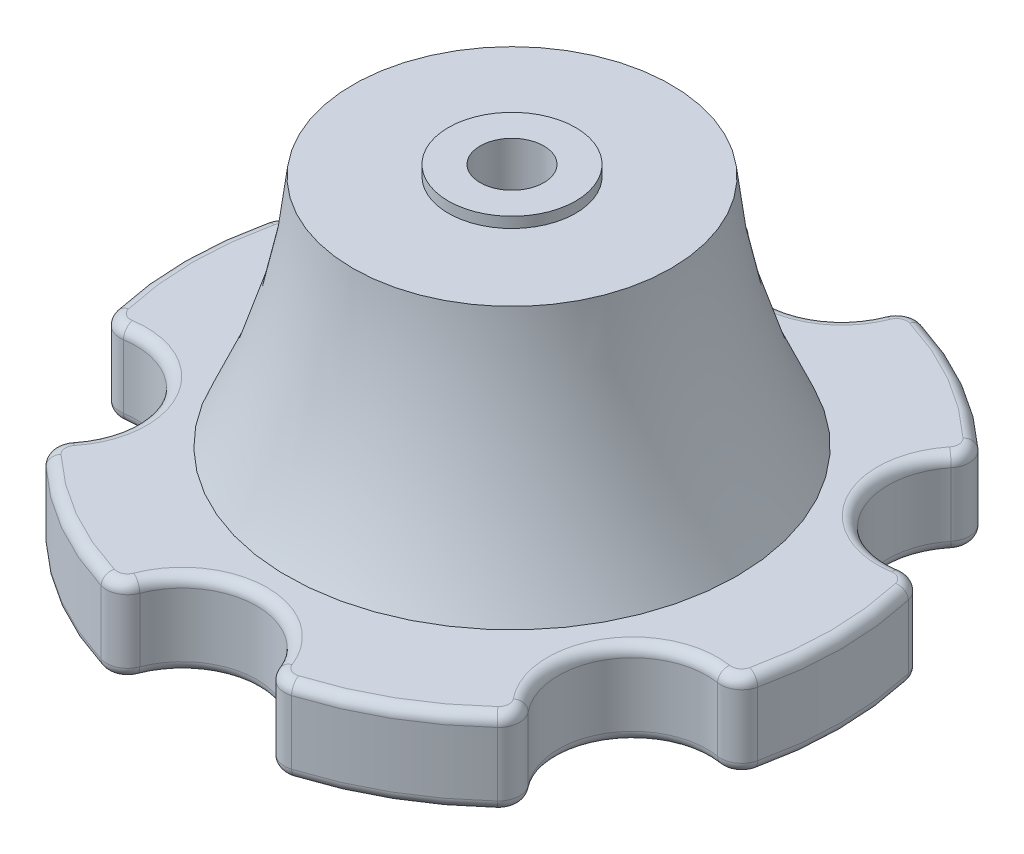
SolidWorks part; units mm, degrees
ref_plane "Спереди" through (0, 0, 0) normal (0, 0, 1) x (1, 0, 0)
ref_plane "Сверху" through (0, 0, 0) normal (0, 1, 0) x (1, 0, 0)
ref_plane "Справа" through (0, 0, 0) normal (1, 0, 0) x (0, 0, -1)
sketch "Эскиз1" plane through (0, 0, 0) normal (0, 1, 0) x (1, 0, 0)
  circle A0 centre (0, 0) radius 15.53 construction
  arc A1 (-3.4777, 15.1356) -> (3.4777, 15.1356) centre (0, 15.53) ccw
  arc A2 (3.4777, 15.1356) -> (11.369, 10.5796) centre (0, 0) cw
  arc A3 (11.369, 10.5796) -> (14.8467, 4.556) centre (13.4494, 7.765) ccw
  arc A4 (14.8467, 4.556) -> (14.8467, -4.556) centre (0, 0) cw
  arc A5 (14.8467, -4.556) -> (11.369, -10.5796) centre (13.4494, -7.765) ccw
  arc A6 (11.369, -10.5796) -> (3.4777, -15.1356) centre (0, 0) cw
  arc A7 (3.4777, -15.1356) -> (-3.4777, -15.1356) centre (0, -15.53) ccw
  arc A8 (-3.4777, -15.1356) -> (-11.369, -10.5796) centre (0, 0) cw
  arc A9 (-11.369, -10.5796) -> (-14.8467, -4.556) centre (-13.4494, -7.765) ccw
  arc A10 (-14.8467, -4.556) -> (-14.8467, 4.556) centre (0, 0) cw
  arc A11 (-14.8467, 4.556) -> (-11.369, 10.5796) centre (-13.4494, 7.765) ccw
  arc A12 (-11.369, 10.5796) -> (-3.4777, 15.1356) centre (0, 0) cw
  point P30 (0, 0)
  dimension "D1" = 3.5
  dimension "D3" = 6
  dimension "D2" = 15.53
extrude "Бобышка-Вытянуть1" add sketch "Эскиз1" along normal blind 15
sketch "Эскиз2" plane through (0, 0, 0) normal (0, 0, 1) x (1, 0, 0)
  line L0 (0, -1000) -> (0, 49000) construction
  line L1 (-15.6, 31) -> (-15.6, 4)
  line L2 (-15.6, 31) -> (-10.6, 31)
  line L3 (-15.6, 4) -> (-10.6, 4)
  line L4 (-3.4777, 0) -> (3.4777, 0) construction
  arc A0 (-10.6, 31) -> (-10.6, 4) centre (-37.3909, 17.5) cw
  dimension "D4" = 30
  dimension "D1" = 15.6
  dimension "D2" = 27
  dimension "D3" = 5
  dimension "D5" = 4
revolve "Вырез-Повернуть1" cut sketch "Эскиз2" angle 360 about L0
sketch "Эскиз3" plane through (0, 0, 0) normal (0, -1, 0) x (1, 0, 0)
  circle A0 centre (0, 0) radius 1.5
  dimension "D1" = 3
extrude "Вырез-Вытянуть1" cut sketch "Эскиз3" against normal blind 15
sketch "Эскиз4" plane through (0, 0, 0) normal (0, -1, 0) x (1, 0, 0)
  line L1 (1.5877, 2.75) -> (-1.5877, 2.75)
  line L2 (-1.5877, 2.75) -> (-3.1754, 0)
  line L3 (-3.1754, 0) -> (-1.5877, -2.75)
  line L4 (-1.5877, -2.75) -> (1.5877, -2.75)
  line L5 (1.5877, -2.75) -> (3.1754, 0)
  line L6 (3.1754, 0) -> (1.5877, 2.75)
  circle A1 centre (0, 0) radius 2.75 construction
  dimension "D1" = 5.5
extrude "Вырез-Вытянуть2" cut sketch "Эскиз4" against normal blind 4
fillet "Скругление1" radius 1 12 edges at (-3.4777, 2, -15.1356) (-11.369, 2, -10.5796) (3.4777, 2, -15.1356) (11.369, 2, -10.5796) (14.8467, 2, -4.556) (14.8467, 2, 4.556) (11.369, 2, 10.5796) (3.4777, 2, 15.1356) (-3.4777, 2, 15.1356) (-14.8467, 2, -4.556) (-11.369, 2, 10.5796) (-14.8467, 2, 4.556)
fillet "Скругление2" radius 0.5 48 edges at (10.4183, 4, 6.015) (10.9451, 4, 10.6598) (7.765, 4, 13.4494) (3.7592, 4, 14.8086) (0, 4, 12.03) (-3.7592, 4, 14.8086) (-7.765, 4, 13.4494) (-10.9451, 4, 10.6598) (-10.4183, 4, 6.015) (-14.7042, 4, 4.1488) (-15.53, 4, 0) (-14.7042, 4, -4.1488) (-10.4183, 4, -6.015) (-10.9451, 4, -10.6598) (-7.765, 4, -13.4494) (-3.7592, 4, -14.8086) (0, 4, -12.03) (3.7592, 4, -14.8086) (7.765, 4, -13.4494) (10.9451, 4, -10.6598) (10.4183, 4, -6.015) (14.7042, 4, -4.1488) (15.53, 4, 0) (-14.7042, 0, -4.1488) (-10.4183, 0, -6.015) (-10.9451, 0, -10.6598) (-7.765, 0, -13.4494) (-3.7592, 0, -14.8086) (0, 0, -12.03) (3.7592, 0, -14.8086) (7.765, 0, -13.4494) (10.9451, 0, -10.6598) (10.4183, 0, -6.015) (14.7042, 0, -4.1488) (15.53, 0, 0) (14.7042, 0, 4.1488) (10.4183, 0, 6.015) (10.9451, 0, 10.6598) (7.765, 0, 13.4494) (3.7592, 0, 14.8086) (0, 0, 12.03) (-3.7592, 0, 14.8086) (-7.765, 0, 13.4494) (-10.9451, 0, 10.6598) (-10.4183, 0, 6.015) (-14.7042, 0, 4.1488) (14.7042, 4, 4.1488) (-15.53, 0, 0)
sketch "Эскиз5" plane through (0, 15, 0) normal (0, 1, 0) x (1, 0, 0)
  circle A0 centre (0, 0) radius 3
  circle A1 centre (0, 0) radius 1.5
  circle A2 centre (0, 0) radius 1.5 construction
  dimension "D1" = 6
extrude "Бобышка-Вытянуть2" add sketch "Эскиз5" along normal blind 0.5
